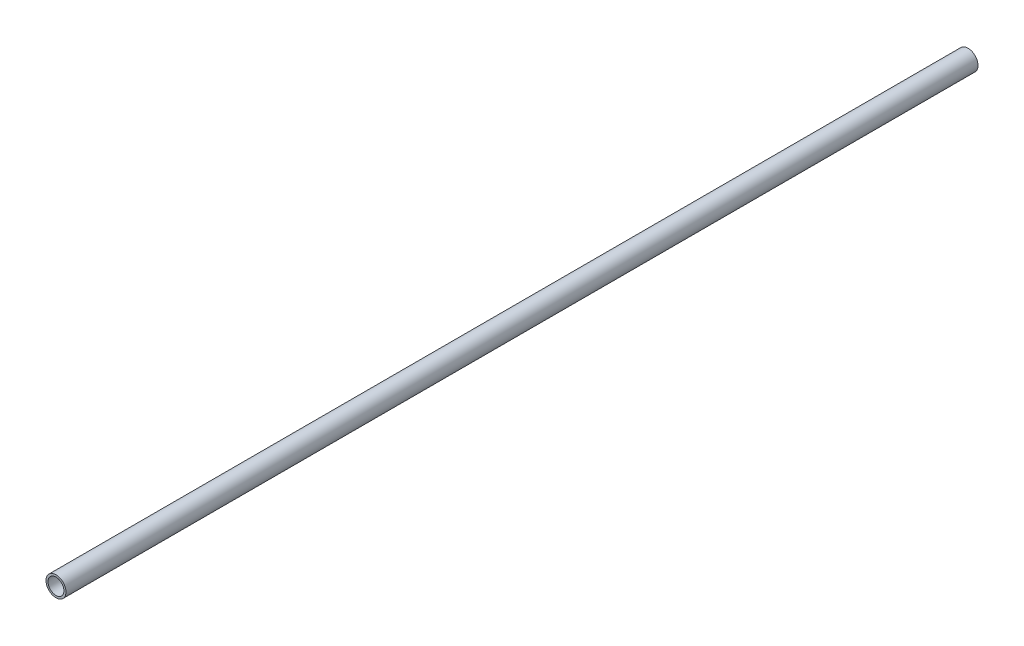
SolidWorks part; units mm, degrees
material "Cast Carbon Steel"
ref_plane "Front Plane" through (0, 0, 0) normal (0, 0, 1) x (1, 0, 0)
ref_plane "Top Plane" through (0, 0, 0) normal (0, 1, 0) x (1, 0, 0)
ref_plane "Right Plane" through (0, 0, 0) normal (1, 0, 0) x (0, 0, -1)
sketch "Sketch1" plane through (0, 0, 0) normal (0, 0, 1) x (1, 0, 0)
  circle A0 centre (0, 0) radius 13.3223
  circle A1 centre (0, 0) radius 16.7005
extrude "Boss-Extrude1" add sketch "Sketch1" against normal blind 1524
